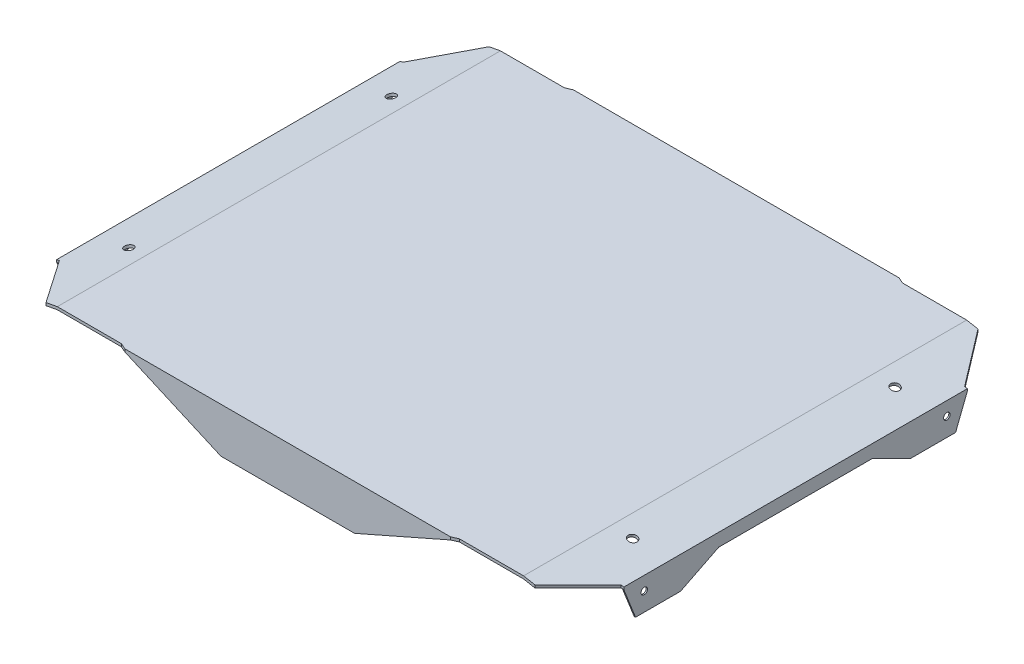
SolidWorks part; units mm, degrees
material "6061-T6 (SS)"
ref_plane "Plan de face" through (0, 0, 0) normal (0, 0, 1) x (1, 0, 0)
ref_plane "Plan de dessus" through (0, 0, 0) normal (0, 1, 0) x (1, 0, 0)
ref_plane "Plan de droite" through (0, 0, 0) normal (1, 0, 0) x (0, 0, -1)
sketch "Esquisse1" plane through (0, 0, 0) normal (0, 1, 0) x (1, 0, 0)
  line L1 (0, 0) -> (416, 0)
  line L2 (0, 0) -> (0, 329)
  line L3 (0, 329) -> (416, 329)
  line L4 (416, 0) -> (416, 329)
  dimension "D1" = 416
  dimension "D2" = 329
extrude "Boss.-Extru.1" add sketch "Esquisse1" against normal blind 33
sketch "Esquisse2" plane through (0, 0, 0) normal (0, 1, 0) x (1, 0, 0)
  line L0 (327.4174, 0) -> (332, 2)
  line L1 (0, 0) -> (416, 0) construction
  line L2 (332, 2) -> (416, 2)
  line L3 (416, 0) -> (416, 329) construction
  line L4 (416, 2) -> (416, 0)
  line L5 (416, 0) -> (327.4174, 0)
  line L6 (88.5826, 0) -> (84, 2)
  line L7 (84, 2) -> (0, 2)
  line L8 (0, 329) -> (0, 0) construction
  line L9 (0, 2) -> (0, 0)
  line L10 (0, 0) -> (88.5826, 0)
  line L11 (88.5826, 329) -> (84, 327)
  line L12 (416, 329) -> (0, 329) construction
  line L13 (84, 327) -> (0, 327)
  line L14 (0, 327) -> (0, 329)
  line L15 (0, 329) -> (88.5826, 329)
  line L16 (327.4174, 329) -> (332, 327)
  line L17 (332, 327) -> (416, 327)
  line L18 (416, 327) -> (416, 329)
  line L19 (416, 329) -> (327.4174, 329)
  dimension "D1" = 2
  dimension "D2" = 5
  dimension "D3" = 5
  dimension "D4" = 2
  dimension "D5" = 5
  dimension "D6" = 5
  dimension "D7" = 2
  dimension "D8" = 2
  dimension "D9" = 248
  dimension "D10" = 248
  dimension "D11" = 84
  dimension "D12" = 84
extrude "Enlèv. mat.-Extru.1" cut sketch "Esquisse2" against normal through all
sketch "Esquisse3" plane through (0, 0, 0) normal (0, 1, 0) x (1, 0, 0)
  line L0 (416, 2) -> (332, 2) construction
  line L1 (414, 2) -> (416, 2)
  line L2 (414, 2) -> (414, 38.5125)
  line L3 (414, 38.5125) -> (416, 38.5125)
  line L4 (416, 2) -> (416, 38.5125)
  line L5 (416, 2) -> (416, 327) construction
  line L7 (414, 290.4875) -> (416, 290.4875)
  line L8 (414, 290.4875) -> (414, 327)
  line L9 (414, 327) -> (416, 327)
  line L10 (416, 290.4875) -> (416, 327)
  line L11 (0, 327) -> (2, 327)
  line L12 (0, 327) -> (0, 290.4875)
  line L13 (0, 290.4875) -> (2, 290.4875)
  line L14 (2, 327) -> (2, 290.4875)
  line L15 (0, 2) -> (2, 2)
  line L16 (0, 2) -> (0, 38.5125)
  line L17 (0, 38.5125) -> (2, 38.5125)
  line L18 (2, 2) -> (2, 38.5125)
  dimension "D1" = 2
  dimension "D2" = 2
  dimension "D3" = 2
  dimension "D4" = 2
  dimension "D5" = 36.5125
  dimension "D6" = 36.5125
  dimension "D7" = 36.5125
  dimension "D8" = 36.5125
extrude "Enlèv. mat.-Extru.2" cut sketch "Esquisse3" against normal through all
ref_plane "Plan1" through (0, 0, -38.5125) normal (0, 0, 1) x (1, 0, 0)
sketch "Esquisse7" plane through (0, 0, -38.5125) normal (0, 0, 1) x (1, 0, 0)
  line L0 (416, -6.8575) -> (379, 0)
  line L1 (416, -33) -> (416, 0) construction
  line L2 (379, 0) -> (416, 0)
  line L3 (416, 0) -> (416, -6.8575)
  line L4 (0, -6.8575) -> (37, 0)
  line L5 (0, -33) -> (0, 0) construction
  line L6 (37, 0) -> (0, 0)
  line L7 (0, 0) -> (0, -6.8575)
  dimension "D1" = 10.5
  dimension "D2" = 10.5
  dimension "D3" = 47
  dimension "D4" = 47
extrude "Enlèv. mat.-Extru.3" cut sketch "Esquisse7" against normal through all and the other way through all
sketch "Esquisse15" plane through (0, 0, -327) normal (0, 0, -1) x (-1, 0, 0)
  line L0 (-84, -33) -> (-2, -33)
  line L1 (-2, -33) -> (-2, -8.4869)
  line L2 (-2, -33) -> (-2, -6.4869) construction
  line L3 (-2, -8.4869) -> (-37, -2)
  line L4 (-37, -2) -> (-84, -2)
  line L5 (-84, -33) -> (-84, 0) construction
  line L6 (-84, -2) -> (-84, -33)
  line L7 (-37, 0) -> (-84, 0) construction
  line L9 (-414, -33) -> (-414, -8.4869)
  line L10 (-414, -33) -> (-414, -6.4869) construction
  line L11 (-414, -8.4869) -> (-379, -2)
  line L12 (-379, -2) -> (-332, -2)
  line L13 (-332, -33) -> (-332, 0) construction
  line L14 (-332, -2) -> (-332, -33)
  line L15 (-332, -33) -> (-414, -33)
  line L16 (-332, 0) -> (-379, 0) construction
  dimension "D1" = 2
  dimension "D2" = 2
  dimension "D3" = 2
  dimension "D4" = 2
extrude "Enlèv. mat.-Extru.11" cut sketch "Esquisse15" against normal through all
sketch "Esquisse8" plane through (1.2288, -6.6298, 0) normal (-0.1822, 0.9833, 0) x (0.9833, 0.1822, 0)
  line L0 (0.7844, 38.5125) -> (27.9337, 2)
  line L1 (36.3804, 2) -> (0.7844, 2) construction
  line L2 (27.9337, 2) -> (0.7844, 2)
  line L3 (0.7844, 2) -> (0.7844, 38.5125)
  line L4 (0.7844, 290.4875) -> (27.9337, 327)
  line L5 (0.7844, 327) -> (36.3804, 327) construction
  line L6 (27.9337, 327) -> (0.7844, 327)
  line L7 (0.7844, 327) -> (0.7844, 290.4875)
  dimension "D1" = 45.5
  dimension "D2" = 45.5
extrude "Enlèv. mat.-Extru.4" cut sketch "Esquisse8" along direction (0, -1, 0) on the side against the normal through all
sketch "Esquisse9" plane through (12.5865, 67.9107, 0) normal (0.1822, 0.9833, 0) x (0.9833, -0.1822, 0)
  line L0 (408.2497, 290.4875) -> (381.1003, 327)
  line L1 (372.6536, 327) -> (408.2497, 327) construction
  line L2 (381.1003, 327) -> (408.2497, 327)
  line L3 (408.2497, 327) -> (408.2497, 290.4875)
  line L4 (408.2497, 38.5125) -> (381.1003, 2)
  line L5 (408.2497, 2) -> (372.6536, 2) construction
  line L6 (381.1003, 2) -> (408.2497, 2)
  line L7 (408.2497, 2) -> (408.2497, 38.5125)
  dimension "D1" = 45.5
  dimension "D2" = 45.5
extrude "Enlèv. mat.-Extru.5" cut sketch "Esquisse9" along direction (0, -1, 0) on the side against the normal through all
sketch "Esquisse10" plane through (416, 0, 0) normal (1, 0, 0) x (0, 0, -1)
  line L0 (290.4875, -33) -> (290.4875, -6.8575) construction
  line L1 (38.5125, -33) -> (290.4875, -33)
  line L2 (38.5125, -33) -> (38.5125, -30.3575)
  line L3 (38.5125, -30.3575) -> (290.4875, -30.3575)
  line L4 (290.4875, -33) -> (290.4875, -30.3575)
  line L5 (290.4875, -6.8575) -> (38.5125, -6.8575) construction
  dimension "D1" = 23.5
extrude "Enlèv. mat.-Extru.6" cut sketch "Esquisse10" against normal through all
sketch "Esquisse16" plane through (84, 0, 0) normal (-1, 0, 0) x (0, 0, 1)
  line L0 (-290.4875, -30.3575) -> (-290.4875, -33)
  line L1 (-290.4875, -33) -> (-327, -33)
  line L2 (-327, -33) -> (-327, -2)
  line L3 (-327, -2) -> (-2, -2)
  line L4 (-2, -2) -> (-2, -33)
  line L5 (-2, -33) -> (-38.5125, -33)
  line L6 (-38.5125, -33) -> (-38.5125, -30.3575)
  line L7 (-38.5125, -30.3575) -> (-290.4875, -30.3575)
extrude "Enlèv. mat.-Extru.12" cut sketch "Esquisse16" against normal up to next
ref_plane "Plan3" through (0, 0, 0) normal (0, 0, 1) x (1, 0, 0)
sketch "Esquisse18" plane through (0, 0, 0) normal (0, 0, 1) x (1, 0, 0)
  line L0 (88.5826, 0) -> (327.4174, 0) construction
  line L1 (327.4174, -33) -> (335.4174, -33)
  line L2 (327.4174, -33) -> (327.4174, -2)
  line L3 (327.4174, -2) -> (335.4174, -2)
  line L4 (335.4174, -33) -> (335.4174, -2)
  line L5 (88.5826, -33) -> (80.5826, -33)
  line L6 (88.5826, -33) -> (88.5826, -2)
  line L7 (88.5826, -2) -> (80.5826, -2)
  line L8 (80.5826, -33) -> (80.5826, -2)
  dimension "D1" = 2
  dimension "D2" = 2
  dimension "D3" = 8
  dimension "D4" = 8
extrude "Enlèv. mat.-Extru.14" cut sketch "Esquisse18" against normal blind 600
sketch "Esquisse20" plane through (327.4174, 0, 0) normal (1, 0, 0) x (0, 0, -1)
  line L0 (2, -2) -> (0, -2) construction
  line L1 (2, -33) -> (1, -33)
  line L2 (2, -33) -> (2, -2)
  line L3 (2, -2) -> (1, -2)
  line L4 (1, -33) -> (1, -2)
  line L5 (329, -2) -> (327, -2) construction
  line L6 (327, -33) -> (328, -33)
  line L7 (327, -33) -> (327, -2)
  line L8 (327, -2) -> (328, -2)
  line L9 (328, -33) -> (328, -2)
  dimension "D1" = 1
  dimension "D2" = 1
extrude "Enlèv. mat.-Extru.16" cut sketch "Esquisse20" against normal through all
sketch "Esquisse19" plane through (0, 0, 0) normal (0, 0, 1) x (1, 0, 0)
  line L0 (88.5826, -2) -> (158.9976, -33)
  line L1 (88.5826, -33) -> (327.4174, -33) construction
  line L2 (158.9976, -33) -> (88.5826, -33)
  line L3 (88.5826, -33) -> (88.5826, -2)
  line L4 (327.4174, -2) -> (256.9976, -33)
  line L5 (256.9976, -33) -> (327.4174, -33)
  line L6 (327.4174, -33) -> (327.4174, -2)
  dimension "D1" = 98
  dimension "D2" = 70.415
extrude "Enlèv. mat.-Extru.15" cut sketch "Esquisse19" against normal through all
sketch "Esquisse21" plane through (0, 0, -290.4875) normal (0, 0, -1) x (-1, 0, 0)
  line L0 (-414, -30.3575) -> (-416, -30.3575) construction
  line L1 (-414, -8.4869) -> (-415, -8.4869)
  line L2 (-414, -8.4869) -> (-414, -30.3575)
  line L3 (-414, -30.3575) -> (-415, -30.3575)
  line L4 (-415, -8.4869) -> (-415, -30.3575)
  line L5 (0, -30.3575) -> (-2, -30.3575) construction
  line L6 (-2, -8.4869) -> (-1, -8.4869)
  line L7 (-2, -8.4869) -> (-2, -30.3575)
  line L8 (-2, -30.3575) -> (-1, -30.3575)
  line L9 (-1, -8.4869) -> (-1, -30.3575)
  dimension "D1" = 1
  dimension "D2" = 1
extrude "Enlèv. mat.-Extru.17" cut sketch "Esquisse21" against normal through all
sketch "Esquisse22" plane through (416, 0, 0) normal (1, 0, 0) x (0, 0, -1)
  line L0 (38.5125, -8.4869) -> (47.1104, -30.3575)
  line L1 (290.4875, -30.3575) -> (38.5125, -30.3575) construction
  line L2 (47.1104, -30.3575) -> (38.5125, -30.3575)
  line L3 (38.5125, -30.3575) -> (38.5125, -8.4869)
  line L4 (290.4875, -8.4869) -> (281.8896, -30.3575)
  line L5 (281.8896, -30.3575) -> (290.4875, -30.3575)
  line L6 (290.4875, -30.3575) -> (290.4875, -8.4869)
  line L7 (80.1104, -30.3575) -> (108.1454, -16.3575)
  line L8 (108.1454, -16.3575) -> (220.6454, -16.3575)
  line L9 (220.6454, -16.3575) -> (248.8896, -30.3575)
  line L10 (248.8896, -30.3575) -> (80.1104, -30.3575)
  line L11 (38.5125, -30.3575) -> (38.5125, -6.8575) construction
  line L12 (290.4875, -30.3575) -> (290.4875, -6.8575) construction
  dimension "D1" = 23.5
  dimension "D2" = 23.5
  dimension "D3" = 112.5
  dimension "D4" = 33
  dimension "D5" = 33
  dimension "D6" = 28.035
  dimension "D7" = 14
extrude "Enlèv. mat.-Extru.18" cut sketch "Esquisse22" against normal through all
hole_wizard "Dégagement 1/41" positions "Esquisse23" profile "Esquisse24" hole size "1/4" standard "Ansi Inch" end condition up to next
sketch "Esquisse23" plane through (12.5865, 67.9107, 0) normal (0.1822, 0.9833, 0) x (0.9833, -0.1822, 0)
  line L1 (372.6536, 327) -> (372.6536, 2) construction
  line L2 (372.6536, 327) -> (381.1003, 327) construction
  point P0 (386.6536, 68.25)
  point P2 (386.6536, 260.75)
  dimension "D1" = 192.5
  dimension "D2" = 14
  dimension "D3" = 14
  dimension "D4" = 66.25
sketch "Esquisse24" plane through (392.7656, -2.5513, -68.25) normal (0, 0, 1) x (-0.9833, 0.1822, 0)
  line L0 (0, 0) -> (0, 1.9665)
  line L1 (0, 1.9665) -> (3.2639, 1.9665)
  line L2 (3.2639, 1.9665) -> (3.2639, 0)
  line L5 (3.2639, 0) -> (0, 0)
  line L11 (0, -6.35) -> (0, 107.95) construction
  dimension "Diamètre du perçage jusqu'au prochain" = 6.5278
  dimension "Profondeur du perçage jusqu'au prochain" = 1.9665
hole_wizard "Dégagement 1/42" positions "Esquisse25" profile "Esquisse26" hole size "1/4" standard "Ansi Inch" end condition up to next
sketch "Esquisse25" plane through (1.2288, -6.6298, 0) normal (-0.1822, 0.9833, 0) x (0.9833, 0.1822, 0)
  line L0 (36.3804, 327) -> (36.3804, 2) construction
  line L1 (36.3804, 2) -> (27.9337, 2) construction
  point P0 (22.3804, 68.25)
  point P2 (22.3804, 260.75)
  point P10 (32.1571, 2)
  dimension "D1" = 14
  dimension "D2" = 14
  dimension "D3" = 192.5
  dimension "D4" = 66.25
sketch "Esquisse26" plane through (23.2344, -2.5513, -68.25) normal (0, 0, 1) x (-0.9833, -0.1822, 0)
  line L0 (0, 0) -> (0, 1.9665)
  line L1 (0, 1.9665) -> (3.2639, 1.9665)
  line L2 (3.2639, 1.9665) -> (3.2639, 0)
  line L5 (3.2639, 0) -> (0, 0)
  line L11 (0, -6.35) -> (0, 107.95) construction
  dimension "Diamètre du perçage jusqu'au prochain" = 6.5278
  dimension "Profondeur du perçage jusqu'au prochain" = 1.9665
sketch "Esquisse27" plane through (0, 0, 0) normal (-1, 0, 0) x (0, 0, 1)
  line L0 (-290.4875, -6.8575) -> (-38.5125, -6.8575) construction
  line L1 (-38.5125, -8.4869) -> (-38.5125, -6.8575) construction
  line L2 (-290.4875, -8.4869) -> (-290.4875, -6.8575) construction
  circle A0 centre (-275.4875, -16.8575) radius 2.3813
  circle A1 centre (-53.5125, -16.8575) radius 2.3812
  dimension "D1" = 4.7625
  dimension "D2" = 4.7625
  dimension "D3" = 10
  dimension "D4" = 10
  dimension "D5" = 15
  dimension "D6" = 15
extrude "Enlèv. mat.-Extru.19" cut sketch "Esquisse27" against normal up to next
sketch "Esquisse28" plane through (416, 0, 0) normal (1, 0, 0) x (0, 0, -1)
  line L0 (290.4875, -6.8575) -> (38.5125, -6.8575) construction
  line L1 (290.4875, -8.4869) -> (290.4875, -6.8575) construction
  line L2 (38.5125, -8.4869) -> (38.5125, -6.8575) construction
  circle A0 centre (53.5125, -16.8575) radius 2.3812
  circle A1 centre (275.4875, -16.8575) radius 2.3813
  dimension "D1" = 4.7625
  dimension "D2" = 4.7625
  dimension "D3" = 10
  dimension "D4" = 15
  dimension "D5" = 10
  dimension "D6" = 15
extrude "Enlèv. mat.-Extru.20" cut sketch "Esquisse28" against normal up to next
